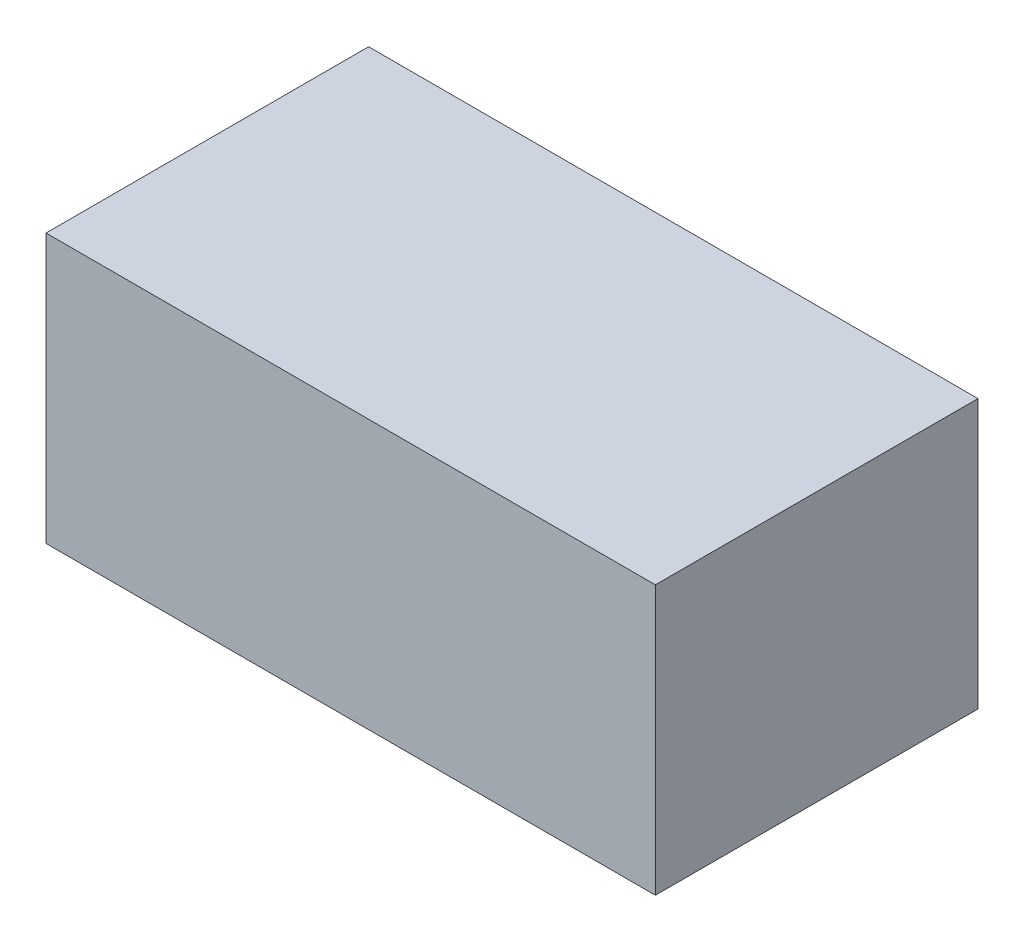
SolidWorks part; units mm, degrees
ref_plane "Front Plane" through (0, 0, 0) normal (0, 0, 1) x (1, 0, 0)
ref_plane "Top Plane" through (0, 0, 0) normal (0, 1, 0) x (1, 0, 0)
ref_plane "Right Plane" through (0, 0, 0) normal (1, 0, 0) x (0, 0, -1)
sketch "Sketch1" plane through (0, 0, 0) normal (0, 0, 1) x (1, 0, 0)
  line L1 (0, 0) -> (1.7, 0)
  line L2 (0, 0) -> (0, 0.75)
  line L3 (0, 0.75) -> (1.7, 0.75)
  line L4 (1.7, 0) -> (1.7, 0.75)
  dimension "D1" = 1.7
  dimension "D2" = 0.75
extrude "Boss-Extrude1" add sketch "Sketch1" along normal blind 0.9
